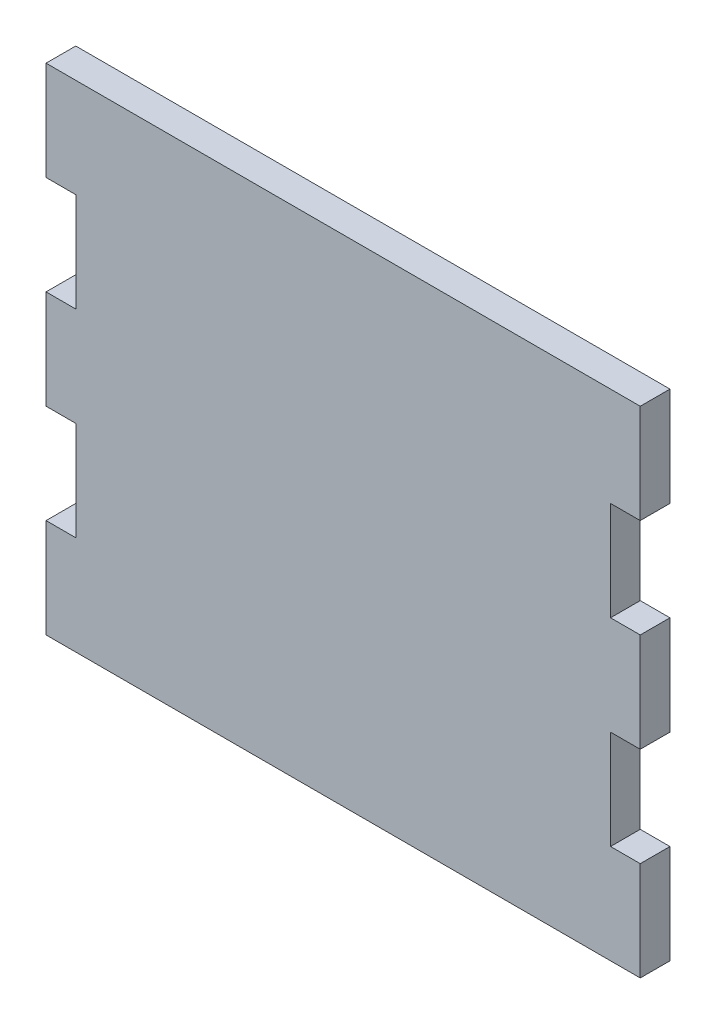
SolidWorks part; units mm, degrees
ref_plane "Plan de face" through (0, 0, 0) normal (0, 0, 1) x (1, 0, 0)
ref_plane "Plan de dessus" through (0, 0, 0) normal (0, 1, 0) x (1, 0, 0)
ref_plane "Plan de droite" through (0, 0, 0) normal (1, 0, 0) x (0, 0, -1)
sketch "Sketch1" plane through (0, 0, 0) normal (0, 0, 1) x (1, 0, 0)
  line L0 (30, 20) -> (30, 10)
  line L1 (-30, -30) -> (30, -30)
  line L2 (-30, -30) -> (-30, 20)
  line L3 (-30, 20) -> (30, 20)
  line L4 (30, -30) -> (30, 20)
  line L5 (27, 10) -> (27, 0)
  line L6 (27, -10) -> (27, -20)
  line L7 (30, 20) -> (12.8579, 20)
  line L8 (30, 10) -> (27, 10)
  line L10 (30, 0) -> (30, -10)
  line L11 (30, 0) -> (27, 0)
  line L12 (30, -10) -> (27, -10)
  line L14 (30, -30) -> (30, -20)
  line L15 (30, -30) -> (27, -30)
  line L16 (30, -20) -> (27, -20)
  line L19 (0, -55) -> (0, 55) construction
  line L20 (-30, -20) -> (-27, -20)
  line L21 (-27, -10) -> (-27, -20)
  line L22 (-30, -10) -> (-27, -10)
  line L23 (-30, 0) -> (-27, 0)
  line L24 (-27, 10) -> (-27, 0)
  line L25 (-30, 10) -> (-27, 10)
  point P0 (0, 0)
  dimension "D1" = 60
  dimension "D2" = 50
  dimension "D3" = 3
  dimension "D4" = 3
  dimension "D5" = 3
  dimension "D6" = 10
  dimension "D7" = 10
  dimension "D8" = 10
  dimension "D9" = 10
  dimension "D10" = 10
extrude "Boss-Extrude1" add sketch "Sketch1" along normal blind 3
